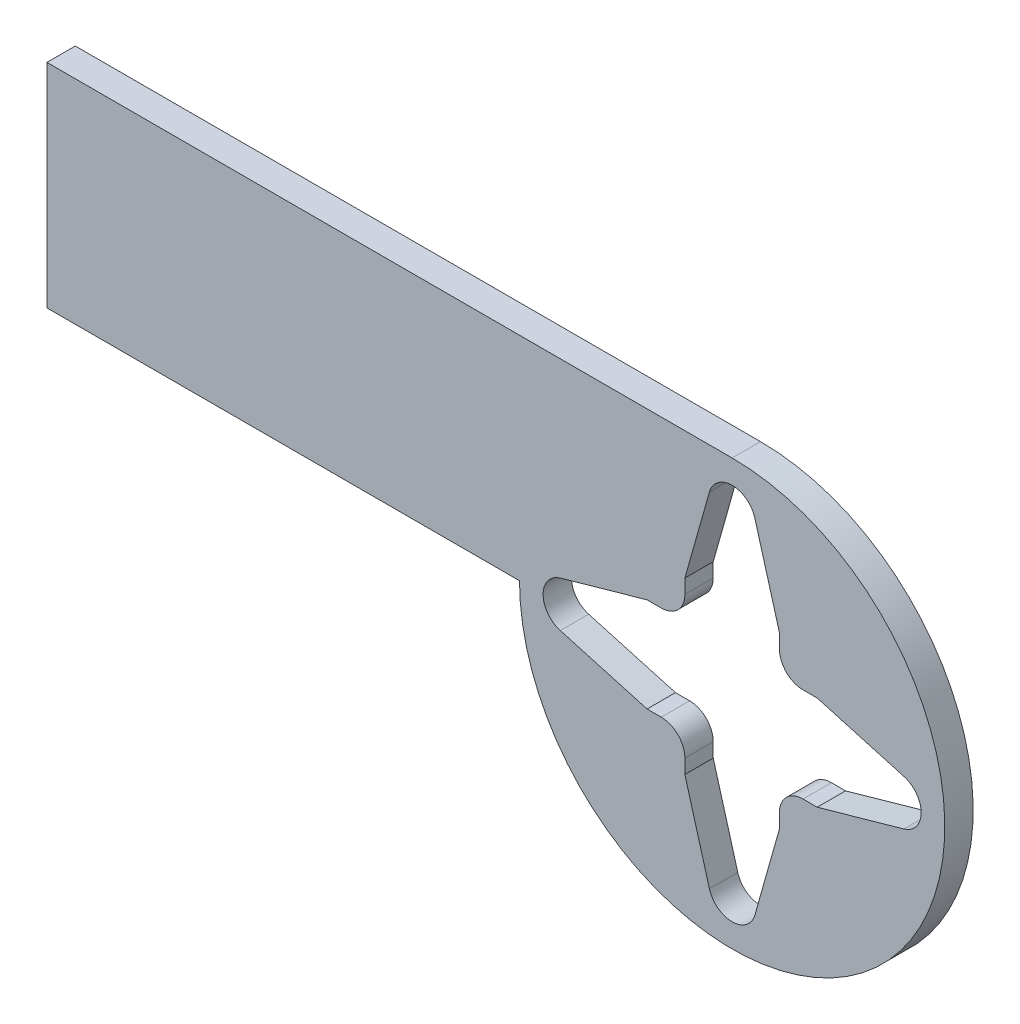
SolidWorks part; units mm, degrees
ref_plane "Front Plane" through (0, 0, 0) normal (0, 0, 1) x (1, 0, 0)
ref_plane "Top Plane" through (0, 0, 0) normal (0, 1, 0) x (1, 0, 0)
ref_plane "Right Plane" through (0, 0, 0) normal (1, 0, 0) x (0, 0, -1)
sketch "Sketch1" plane through (0, 0, 0) normal (0, 0, 1) x (1, 0, 0)
  line L0 (-5, 5) -> (-5, 9)
  line L8 (5, -5) -> (-5, -5)
  line L9 (5, -5) -> (5, 5)
  line L10 (5, 5) -> (-5, 5)
  line L11 (-5, -5) -> (-5, 5)
  line L12 (5, -5) -> (-5, 5) construction
  line L13 (5, 5) -> (-5, -5) construction
  line L14 (-5, 9) -> (-2.4058, 18.1799)
  line L15 (0, -55) -> (0, 55) construction
  line L16 (9, 5) -> (18.1799, 2.4058)
  line L17 (5, 5) -> (5, 9)
  line L18 (55, 0) -> (-55, 0) construction
  line L19 (5, -5) -> (5, -9)
  line L20 (-5, -9) -> (-2.4058, -18.1799)
  line L21 (5, -9) -> (2.4058, -18.1799)
  line L22 (-5, -5) -> (-5, -9)
  line L23 (5, -5) -> (9, -5)
  line L24 (9, -5) -> (18.1799, -2.4058)
  line L25 (-9, -5) -> (-18.1799, -2.4058)
  line L26 (5, 5) -> (9, 5)
  line L27 (-5, -5) -> (-9, -5)
  line L28 (-9, 5) -> (-18.1799, 2.4058)
  line L29 (5, 9) -> (2.4058, 18.1799)
  line L30 (-5, 5) -> (-9, 5)
  line L31 (0, 22.5) -> (-22.5, 0)
  line L32 (-22.5, 0) -> (-22.5, 22.5)
  line L33 (-22.5, 22.5) -> (0, 22.5)
  line L35 (-22.5, 22.5) -> (-72.5, 22.5)
  line L36 (-22.5, 22.5) -> (-22.5, 0)
  line L37 (-22.5, 0) -> (-72.5, 0)
  line L38 (-72.5, 22.5) -> (-72.5, 0)
  circle A0 centre (0, 0) radius 22.5
  circle A1 centre (0, 17.5) radius 2.5
  circle A2 centre (0, -17.5) radius 2.5
  circle A3 centre (17.5, 0) radius 2.5
  circle A4 centre (-17.5, 0) radius 2.5
  circle A5 centre (-7.5, 7.5) radius 2.5
  circle A6 centre (-7.5, -7.5) radius 2.5
  circle A7 centre (7.5, 7.5) radius 2.5
  circle A8 centre (7.5, -7.5) radius 2.5
  arc A9 (-24.8747, 0) -> (-22.3872, -2.25) centre (-24.8747, -2.5) cw
  point P53 (-25.9742, -5)
  point P54 (-22.2598, -3.2792)
  dimension "D1" = 45
  dimension "D3" = 5
  dimension "D5" = 12.5
  dimension "D6" = 5
  dimension "D9" = 5
  dimension "D11" = 2.5
  dimension "D2" = 10
  dimension "D4" = 4
  dimension "D7" = 4
  dimension "D8" = 12.5
  dimension "D10" = 50
extrude "Boss-Extrude1" add sketch "Sketch1" along normal blind 3
